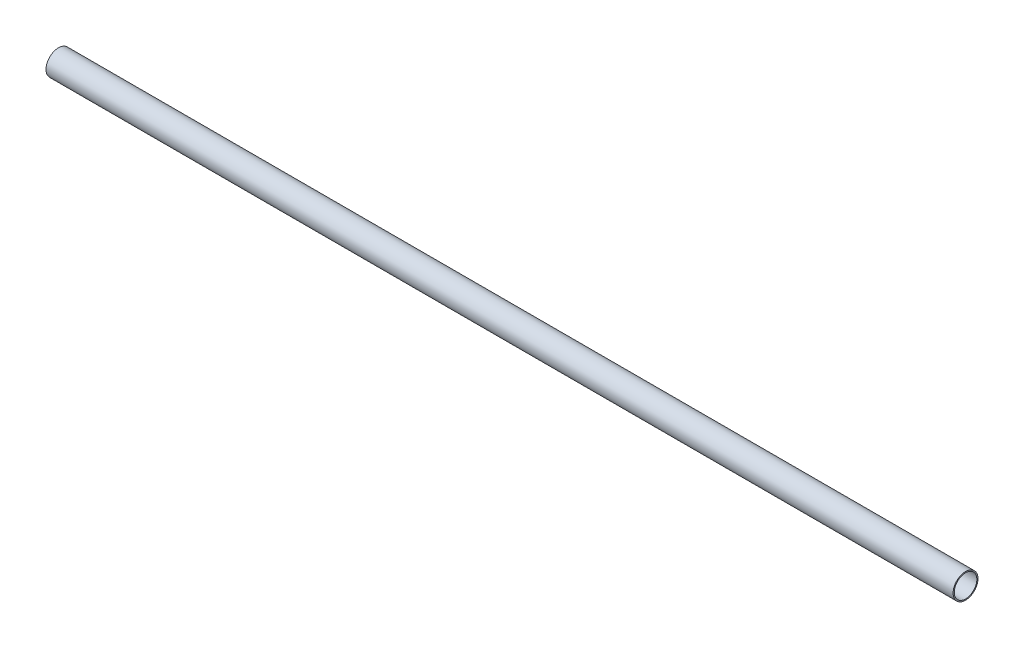
SolidWorks part; units mm, degrees
ref_plane "Front Plane" through (0, 0, 0) normal (0, 0, 1) x (1, 0, 0)
ref_plane "Top Plane" through (0, 0, 0) normal (0, 1, 0) x (1, 0, 0)
ref_plane "Right Plane" through (0, 0, 0) normal (1, 0, 0) x (0, 0, -1)
sketch "Sketch1" plane through (0, 0, 0) normal (1, 0, 0) x (0, 0, -1)
  circle A0 centre (0, 0) radius 9.525
  circle A1 centre (0, 0) radius 8.636
  dimension "D1" = 19.05
  dimension "D2" = 17.272
extrude "Boss-Extrude1" add sketch "Sketch1" along normal up to surface (693.5846 mm away)
equation "\"D1\"= 12.489 - 2 *  ( .25 + 3 / 8 + .312 / 2 ) "
